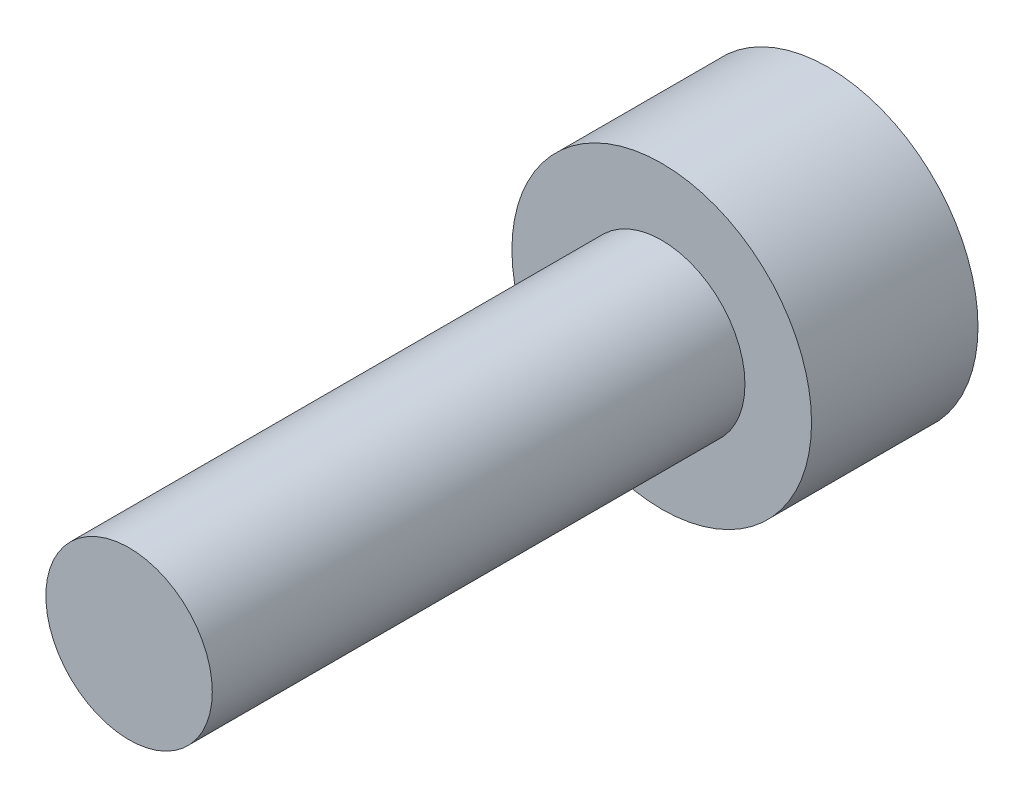
SolidWorks part; units mm, degrees
ref_plane "正面" through (0, 0, 0) normal (0, 0, 1) x (1, 0, 0)
ref_plane "平面" through (0, 0, 0) normal (0, 1, 0) x (1, 0, 0)
ref_plane "右側面" through (0, 0, 0) normal (1, 0, 0) x (0, 0, -1)
sketch "ｽｹｯﾁ1" plane through (0, 0, 0) normal (0, 0, 1) x (1, 0, 0)
  circle A0 centre (0, 0) radius 2.25
  dimension "D1" = 4.5
extrude "ﾎﾞｽ - 押し出し1" add sketch "ｽｹｯﾁ1" along normal blind 2.5
sketch "ｽｹｯﾁ2" plane through (0, 0, 2.5) normal (0, 0, 1) x (1, 0, 0)
  circle A0 centre (0, 0) radius 1.25
  dimension "D1" = 2.5
extrude "ﾎﾞｽ - 押し出し2" add sketch "ｽｹｯﾁ2" along normal blind 8
cosmetic thread "ねじ山1" parameters "D2"=1
sketch "ｽｹｯﾁ3" plane through (0, 0, 0) normal (0, 0, -1) x (-1, 0, 0)
  line L1 (0.8522, -0.7637) -> (1.0875, 0.3562)
  line L2 (1.0875, 0.3562) -> (0.2352, 1.1199)
  line L3 (0.2352, 1.1199) -> (-0.8522, 0.7637)
  line L4 (-0.8522, 0.7637) -> (-1.0875, -0.3562)
  line L5 (-1.0875, -0.3562) -> (-0.2352, -1.1199)
  line L6 (-0.2352, -1.1199) -> (0.8522, -0.7637)
  circle A0 centre (0, 0) radius 0.991 construction
extrude "ｶｯﾄ - 押し出し1" cut sketch "ｽｹｯﾁ3" against normal blind 2
